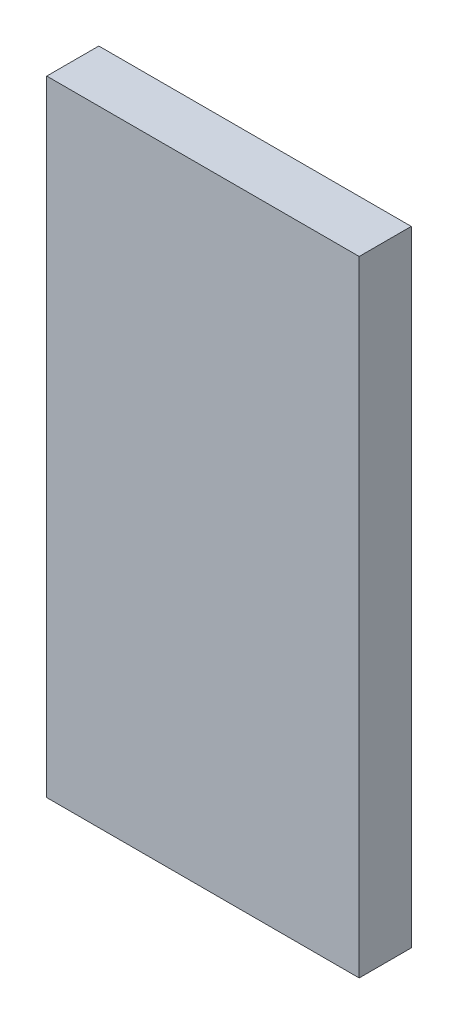
SolidWorks part; units mm, degrees
material "Teak"
ref_plane "Front Plane" through (0, 0, 0) normal (0, 0, 1) x (1, 0, 0)
ref_plane "Top Plane" through (0, 0, 0) normal (0, 1, 0) x (1, 0, 0)
ref_plane "Right Plane" through (0, 0, 0) normal (1, 0, 0) x (0, 0, -1)
sketch "Sketch1" plane through (0, 0, 0) normal (0, 0, 1) x (1, 0, 0)
  line L1 (-12.7, 1181.1) -> (-88.9, 1181.1)
  line L2 (-12.7, 1181.1) -> (-12.7, 1028.7)
  line L3 (-12.7, 1028.7) -> (-88.9, 1028.7)
  line L4 (-88.9, 1181.1) -> (-88.9, 1028.7)
  dimension "D1" = 76.2
  dimension "D2" = 152.4
extrude "Boss-Extrude1" add sketch "Sketch1" along normal blind 12.7
